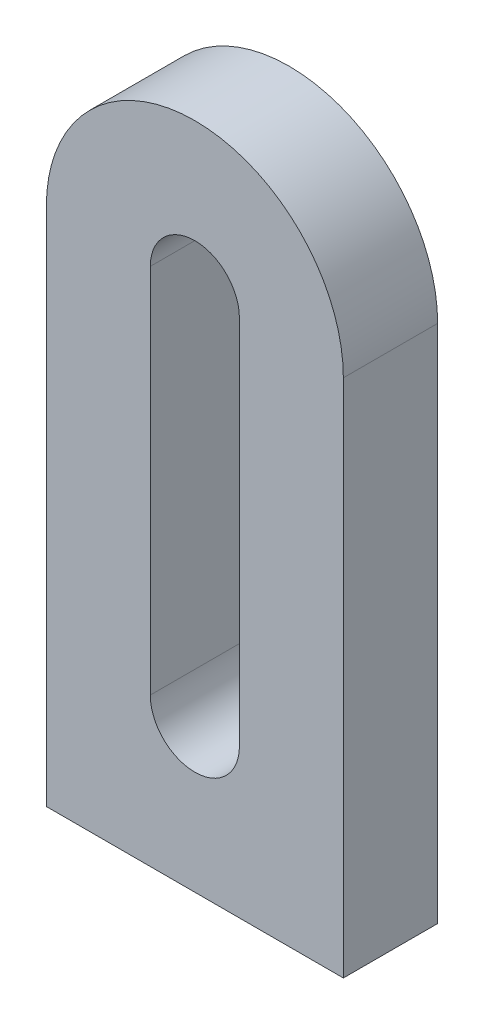
SolidWorks part; units mm, degrees
ref_plane "Alzado" through (0, 0, 0) normal (0, 0, 1) x (1, 0, 0)
ref_plane "Planta" through (0, 0, 0) normal (0, 1, 0) x (1, 0, 0)
ref_plane "Vista lateral" through (0, 0, 0) normal (1, 0, 0) x (0, 0, -1)
sketch "Sketch1" plane through (0, 0, 0) normal (0, 0, 1) x (1, 0, 0)
  line L0 (0, 35) -> (0, 10) construction
  line L2 (-10, 35) -> (-10, 0)
  line L3 (-10, 0) -> (10, 0)
  line L4 (10, 35) -> (10, 0)
  line L5 (-10, 35) -> (10, 0) construction
  line L6 (-10, 0) -> (10, 35) construction
  line L7 (3, 35) -> (3, 10)
  line L8 (-3, 35) -> (-3, 10)
  arc A0 (-10, 35) -> (10, 35) centre (0, 35) cw
  arc A1 (3, 35) -> (-3, 35) centre (0, 35) ccw
  arc A2 (-3, 10) -> (3, 10) centre (0, 10) ccw
  point P4 (0, 17.5)
  point P6 (0, 22.5)
  dimension "D3" = 6
  dimension "D5" = 45
  dimension "D1" = 35
  dimension "D2" = 20
  dimension "D4" = 25
extrude "Boss-Extrude1" add sketch "Sketch1" along normal blind 6.35
